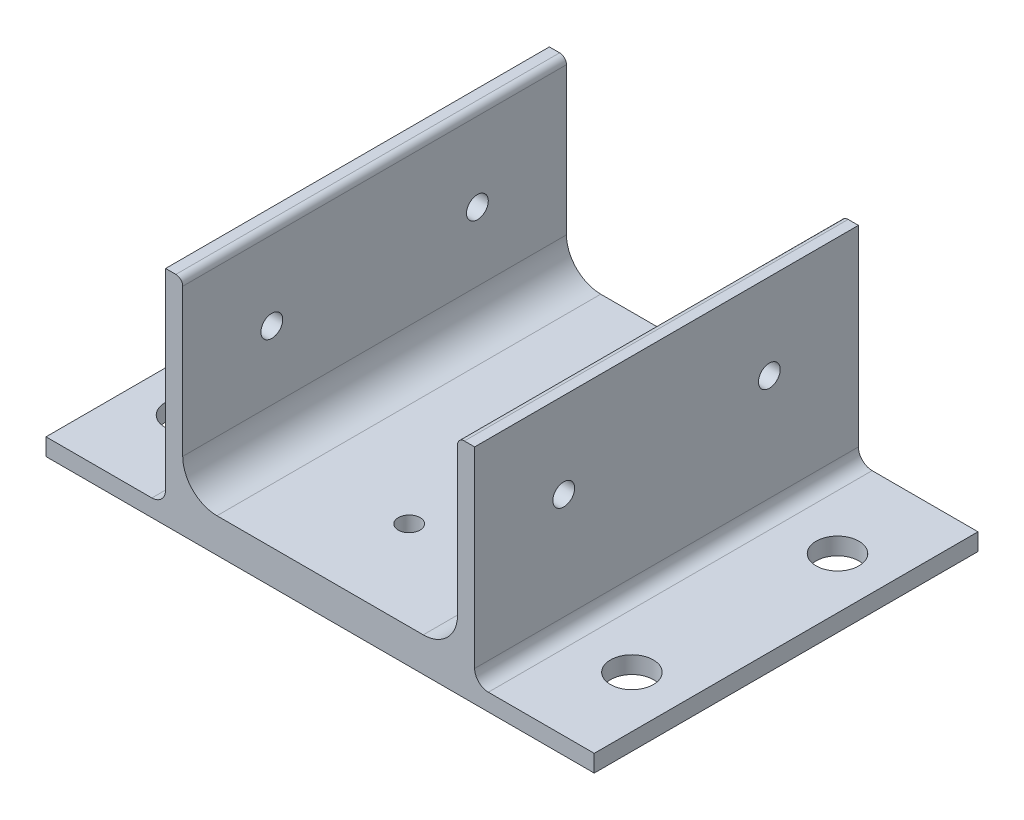
SolidWorks part; units mm, degrees
ref_plane "Front" through (0, 0, 0) normal (0, 0, 1) x (1, 0, 0)
ref_plane "Top" through (0, 0, 0) normal (0, 1, 0) x (1, 0, 0)
ref_plane "Right" through (0, 0, 0) normal (1, 0, 0) x (0, 0, -1)
sketch "Sketch1" plane through (0, 0, 0) normal (0, 0, 1) x (1, 0, 0)
  line L0 (0, 0) -> (0, 34.925)
  line L1 (0, 34.925) -> (-3.175, 34.925)
  line L2 (-3.175, 34.925) -> (-3.175, -3.175)
  line L3 (-3.175, -3.175) -> (34.925, -3.175)
  line L4 (34.925, -3.175) -> (34.925, 0)
  line L5 (34.925, 0) -> (0, 0)
  dimension "Height" = 38.1
  dimension "Width" = 38.1
  dimension "Wall Thickness" = 3.175
sketch "Sketch3" plane through (0, 0, 0) normal (0, 0, 1) x (1, 0, 0)
  line L0 (0, 0) -> (0, 34.925) construction
  line L1 (0, 34.925) -> (-3.175, 34.925) construction
  line L2 (-3.175, 34.925) -> (-3.175, -3.175) construction
  line L3 (-3.175, -3.175) -> (34.925, -3.175) construction
  line L4 (34.925, -3.175) -> (34.925, 0) construction
  line L5 (34.925, 0) -> (0, 0) construction
  line L6 (0, 6.35) -> (0, 33.655)
  line L7 (-1.27, 34.925) -> (-3.175, 34.925)
  line L8 (-3.175, 34.925) -> (-3.175, 0)
  line L9 (-3.175, -3.175) -> (34.925, -3.175)
  line L10 (34.925, -3.175) -> (34.925, -1.27)
  line L11 (33.655, 0) -> (6.35, 0)
  line L12 (-3.175, -3.175) -> (-3.175, 0)
  arc A0 (0, 6.35) -> (6.35, 0) centre (6.35, 6.35) ccw
  arc A1 (34.925, -1.27) -> (33.655, 0) centre (33.655, -1.27) ccw
  arc A2 (0, 33.655) -> (-1.27, 34.925) centre (-1.27, 33.655) ccw
  dimension "D1" = 1.27
  dimension "D2" = 6.35
extrude "Boss-Extrude1" add sketch "Sketch3" along normal blind 71.12
sketch "Sketch4" plane through (0, 0, 0) normal (0, 0, -1) x (-1, 0, 0)
  line L0 (3.175, -3.175) -> (-34.925, -3.175) construction
  line L1 (-25.4635, -3.175) -> (-34.925, -3.175)
  line L2 (-25.4635, -3.175) -> (-25.4635, 0)
  line L3 (-25.4635, 0) -> (-34.925, 0)
  line L4 (-34.925, -3.175) -> (-34.925, 0)
  line L5 (0, 6.35) -> (0, 33.655) construction
  line L6 (-34.925, -3.175) -> (-34.925, -1.27) construction
  dimension "D1" = 3.175
  dimension "D2" = 25.4635
extrude "Cut-Extrude1" cut sketch "Sketch4" against normal through all
sketch "Sketch5" plane through (0, 0, 0) normal (0, 0, -1) x (-1, 0, 0)
  line L0 (-25.4635, -3.175) -> (-54.102, -3.175)
  line L1 (-54.102, -3.175) -> (-54.102, 34.925)
  line L2 (-54.102, 34.925) -> (-50.927, 34.925)
  line L3 (-50.927, 34.925) -> (-50.927, 0)
  line L4 (-50.927, 0) -> (-25.4635, 0)
  line L5 (-25.4635, 0) -> (-25.4635, -3.175)
  line L6 (1.27, 34.925) -> (3.175, 34.925) construction
  dimension "D1" = 25.4635
  dimension "D2" = 3.175
extrude "Boss-Extrude2" add sketch "Sketch5" against normal blind 71.12
fillet "Fillet2" radius 6.35 1 edges at (50.927, 0, 35.56)
fillet "Fillet4" radius 1.27 1 edges at (50.927, 34.925, 35.56)
sketch "Sketch6" plane through (0, -3.175, 0) normal (0, -1, 0) x (1, 0, 0)
  line L1 (-25.3365, 71.12) -> (76.2635, 71.12)
  line L2 (-25.3365, 71.12) -> (-25.3365, 0)
  line L3 (-25.3365, 0) -> (76.2635, 0)
  line L4 (76.2635, 71.12) -> (76.2635, 0)
  line L7 (54.102, 71.12) -> (54.102, 0) construction
  line L8 (44.577, 71.12) -> (6.35, 71.12) construction
  dimension "D1" = 101.6
  dimension "D2" = 71.12
  dimension "D3" = 22.1615
extrude "Boss-Extrude3" add sketch "Sketch6" along normal blind 3.175
sketch "Sketch7" plane through (-3.175, 0, 0) normal (-1, 0, 0) x (0, 0, 1)
  line L0 (71.12, 34.925) -> (0, 34.925) construction
  line L3 (0, 34.925) -> (0, -3.175) construction
  circle A0 centre (16.51, 19.05) radius 2.0193
  circle A1 centre (54.61, 19.05) radius 2.0193
  dimension "D1" = 15.875
  dimension "D4" = 4.0386
  dimension "D2" = 38.1
  dimension "D3" = 16.51
extrude "Cut-Extrude2" cut sketch "Sketch7" against normal through all
sketch "Sketch8" plane through (0, -6.35, 0) normal (0, -1, 0) x (1, 0, 0)
  line L1 (-25.3365, 0) -> (76.2635, 0) construction
  line L2 (76.2635, 0) -> (76.2635, 71.12) construction
  circle A0 centre (25.4635, 16.51) radius 2.0193
  circle A1 centre (25.4635, 54.61) radius 2.0193
  dimension "D1" = 38.1
  dimension "D3" = 4.0386
  dimension "D2" = 16.51
  dimension "D4" = 50.8
extrude "Cut-Extrude3" cut sketch "Sketch8" against normal through all
sketch "Sketch9" plane through (0, -6.35, 0) normal (0, -1, 0) x (1, 0, 0)
  line L0 (76.2635, 71.12) -> (-25.3365, 71.12) construction
  line L1 (76.2635, 0) -> (76.2635, 71.12) construction
  circle A0 centre (-15.8115, 16.51) radius 3.9688
  circle A1 centre (-15.8115, 54.61) radius 3.9688
  circle A2 centre (66.7385, 54.61) radius 3.9687
  circle A3 centre (66.7385, 16.51) radius 3.9687
  dimension "D1" = 7.9375
  dimension "D2" = 38.1
  dimension "D3" = 16.51
  dimension "D4" = 82.55
  dimension "D5" = 9.525
extrude "Cut-Extrude4" cut sketch "Sketch9" against normal through all
fillet "Fillet5" radius 2.54 2 edges at (-3.175, -3.175, 35.56) (54.102, -3.175, 35.56)
sketch "Sketch10" plane through (0, -6.35, 0) normal (0, -1, 0) x (1, 0, 0)
  circle A0 centre (25.4635, 54.61) radius 5.08
  circle A1 centre (25.4635, 16.51) radius 5.08
  dimension "D1" = 10.16
  dimension "D2" = 10.16
extrude "Cut-Extrude5" cut sketch "Sketch10" against normal blind 3.175
equation "\"D1@Sketch3\"=\"Wall Thickness@Sketch1\"*0.4"
equation "\"D2@Sketch3\"=\"Wall Thickness@Sketch1\"*2"
